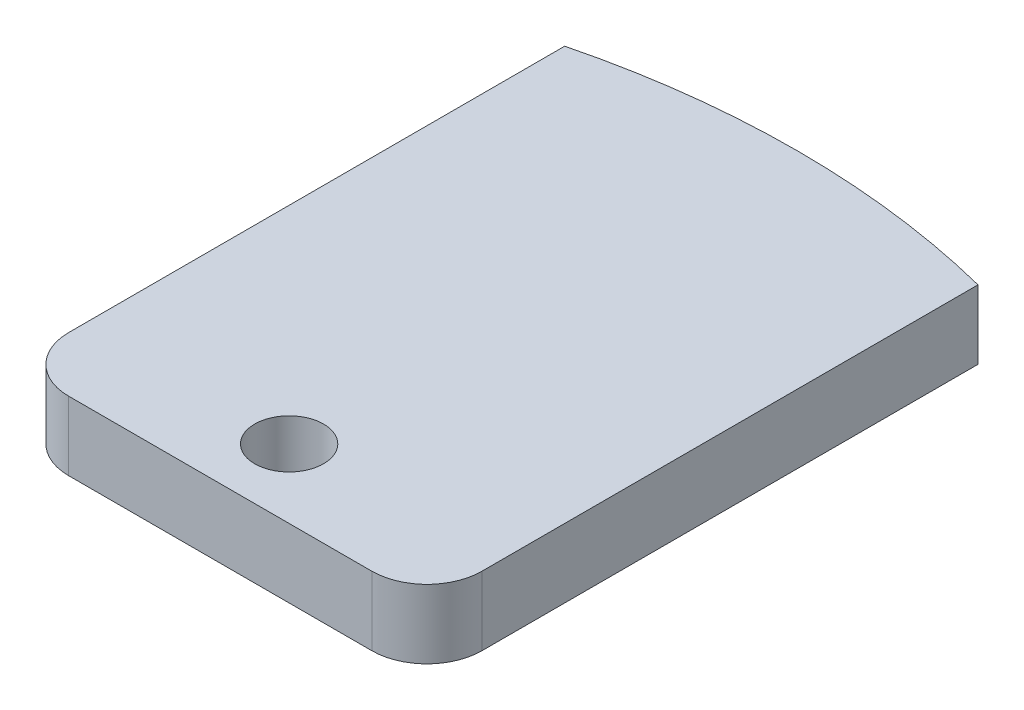
SolidWorks part; units mm, degrees
ref_plane "Front Plane" through (0, 0, 0) normal (0, 0, 1) x (1, 0, 0)
ref_plane "Top Plane" through (0, 0, 0) normal (0, 1, 0) x (1, 0, 0)
ref_plane "Right Plane" through (0, 0, 0) normal (1, 0, 0) x (0, 0, -1)
sketch "Sketch2" plane through (0, 0, 0) normal (0, 1, 0) x (1, 0, 0)
  line L0 (0, -25.4) -> (0, -19.05) construction
  line L1 (-13.97, -25.4) -> (13.97, -25.4)
  line L2 (-19.05, -20.32) -> (-19.05, 25.4)
  line L3 (-19.05, 25.4) -> (19.05, 25.4)
  line L4 (19.05, -20.32) -> (19.05, 25.4)
  line L5 (-19.05, -25.4) -> (19.05, 25.4) construction
  line L6 (-19.05, 25.4) -> (19.05, -25.4) construction
  circle A0 centre (0, -49.8485) radius 77.6224
  arc A1 (13.97, -25.4) -> (19.05, -20.32) centre (13.97, -20.32) ccw
  arc A2 (-13.97, -25.4) -> (-19.05, -20.32) centre (-13.97, -20.32) cw
  circle A3 centre (0, -19.05) radius 3.175
  point P0 (0, 0)
  dimension "D3" = 155.2448
  dimension "D4" = 5.08
  dimension "D6" = 6.35
  dimension "D1" = 50.8
  dimension "D2" = 38.1
  dimension "D5" = 6.35
extrude "Boss-Extrude1" add sketch "Sketch2" along normal mid plane 6.35 contours A2 L1 A1 L4 L3 L2 | L3 A0
equation "\"airframeInnerDiameter\"= 6in"
equation "\"outerDiameter\"= 6.112in"
equation "\"airframeBulkheadThickness\"= 0.125in"
equation "\"payloadAirframeLength\"= 10in"
equation "\"payloadInnerDiameter\"= 6in - 0.056in"
equation "\"payloadOuterDiameter\"= \"airframeInnerDiameter\""
equation "\"payloadLength\"= 11in"
equation "\"payloadBand\"= 2in"
equation "\"payloadOffsetFromAft\"= 6in"
equation "\"upperAirframeLength\"= 25in"
equation "\"recoveryBayInnerDiameter\"= 5.888in"
equation "\"recoveryLength\"= 8in"
equation "\"recoveryBand\"= 2in"
equation "\"recoveryCouplerOuter\"=\"airframeInnerDiameter\""
equation "\"recoveryOffsetFromAft\"= 3in"
equation "\"midAirframeLength\"= 20in"
equation "\"atsLength\"= 11in"
equation "\"atsInner\"= 5.888in"
equation "\"atsBand\"= 2in"
equation "\"atsCouplerOuter\"=\"airframeInnerDiameter\""
equation "\"atsOffsetFromAft\"= 3in"
equation "\"lowerAirframeLength\"= 40in"
equation "\"motorTubeOuterDiameter\"= 4.25in"
equation "\"motorTubeInnerDiameter\"= 4in"
equation "\"motorTubeLength\"= 32in"
equation "\"centeringRingOuterDiameter\"= \"airframeInnerDiameter\""
equation "\"centeringRingInnerDiameter\"= \"motorTubeOuterDiameter\""
equation "\"centeringRingThickness\"= 0.375in"
equation "\"topCenteringRingOffsetFromAft\"= 16.7in"
equation "\"bottomCenteringRingOffsetFromAft\"= 0.3in"
equation "\"finSlotLength\"= 8in"
equation "\"finSlotOffsetFromAft\"= 3in"
equation "\"finSlotWidth\"= 0.187in"
equation "\"motorCasingOuterDiameter\"= 3in"
equation "\"motorCasingCenteringRingThickness\"= 0.25in"
equation "\"D3@Sketch2\"=\"outerDiameter\""
